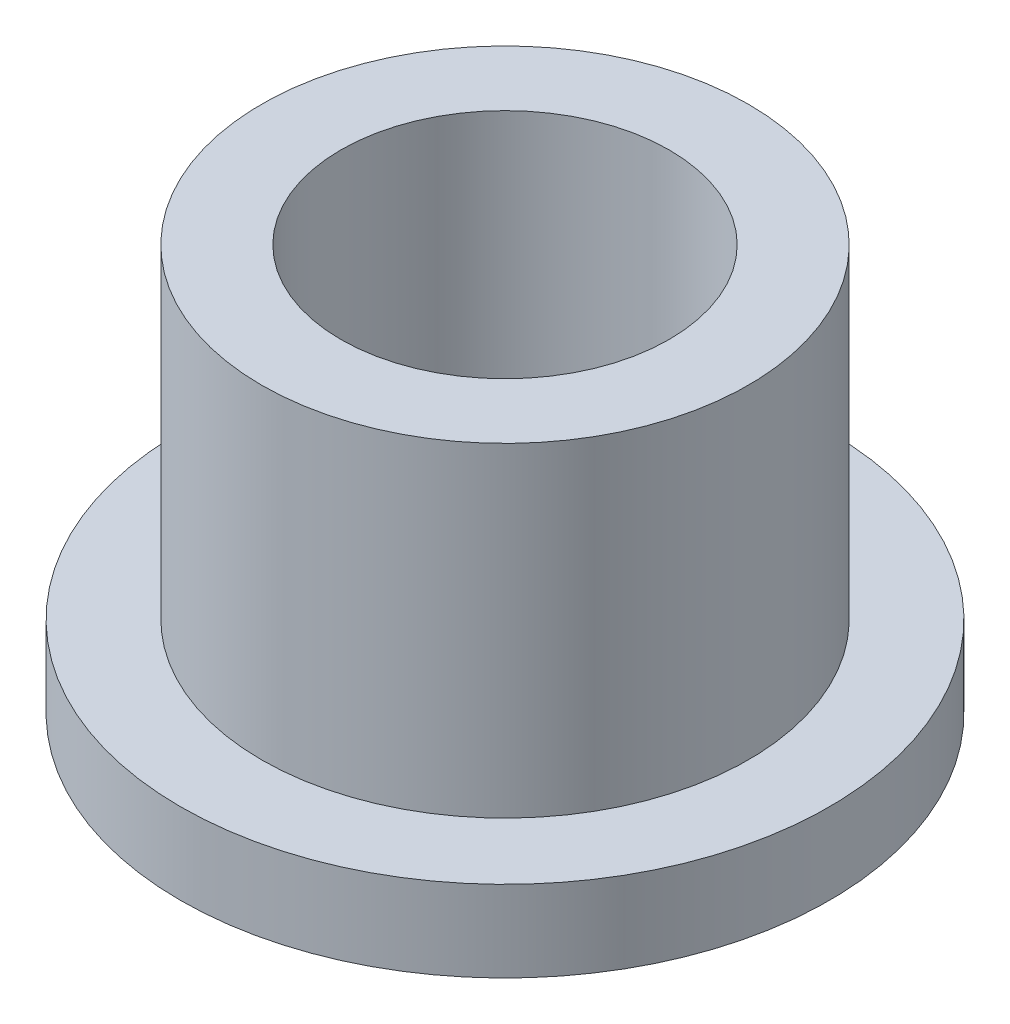
SolidWorks part; units mm, degrees
ref_plane "Front" through (0, 0, 0) normal (0, 0, 1) x (1, 0, 0)
ref_plane "Top" through (0, 0, 0) normal (0, 1, 0) x (1, 0, 0)
ref_plane "Right" through (0, 0, 0) normal (1, 0, 0) x (0, 0, -1)
sketch "Sketch1" plane through (0, 0, 0) normal (0, 1, 0) x (1, 0, 0)
  circle A0 centre (0, 0) radius 3.2131
  circle A1 centre (0, 0) radius 4.7625
  circle A2 centre (0, 0) radius 6.35
  dimension "ID" = 6.4262
  dimension "OD" = 9.525
  dimension "FlangeOD" = 12.7
sketch "Sketch2" plane through (0, 0, 0) normal (0, 1, 0) x (1, 0, 0)
  circle A0 centre (0, 0) radius 3.2131 construction
  circle A1 centre (0, 0) radius 4.7625 construction
  circle A2 centre (0, 0) radius 3.2131
  circle A3 centre (0, 0) radius 4.7625
extrude "Boss-Extrude1" add sketch "Sketch2" along normal blind 7.9375
sketch "Sketch3" plane through (0, 0, 0) normal (0, 1, 0) x (1, 0, 0)
  circle A0 centre (0, 0) radius 6.35 construction
  circle A1 centre (0, 0) radius 4.7625 construction
  circle A2 centre (0, 0) radius 6.35
  circle A3 centre (0, 0) radius 4.7625
extrude "Boss-Extrude2" add sketch "Sketch3" along normal blind 1.5875
